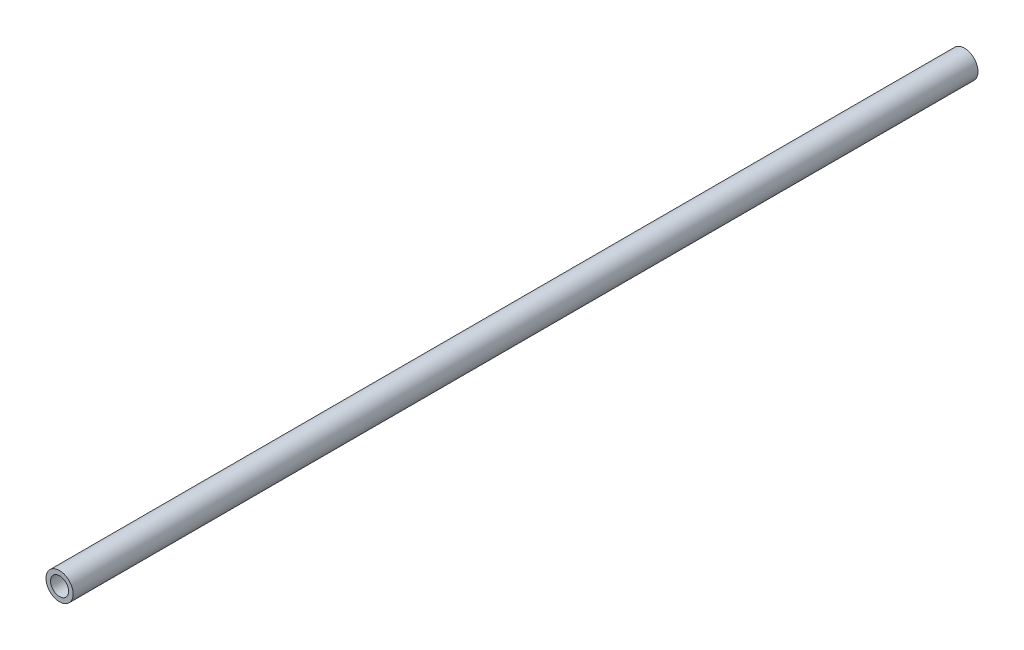
SolidWorks part; units mm, degrees
ref_plane "Front Plane" through (0, 0, 0) normal (0, 0, 1) x (1, 0, 0)
ref_plane "Top Plane" through (0, 0, 0) normal (0, 1, 0) x (1, 0, 0)
ref_plane "Right Plane" through (0, 0, 0) normal (1, 0, 0) x (0, 0, -1)
sketch "Sketch2" plane through (0, 0, 0) normal (0, 0, 1) x (1, 0, 0)
  circle A0 centre (0, 0) radius 7.5
  circle A1 centre (0, 0) radius 5
extrude "Boss-Extrude1" add sketch "Sketch2" along normal blind 500
